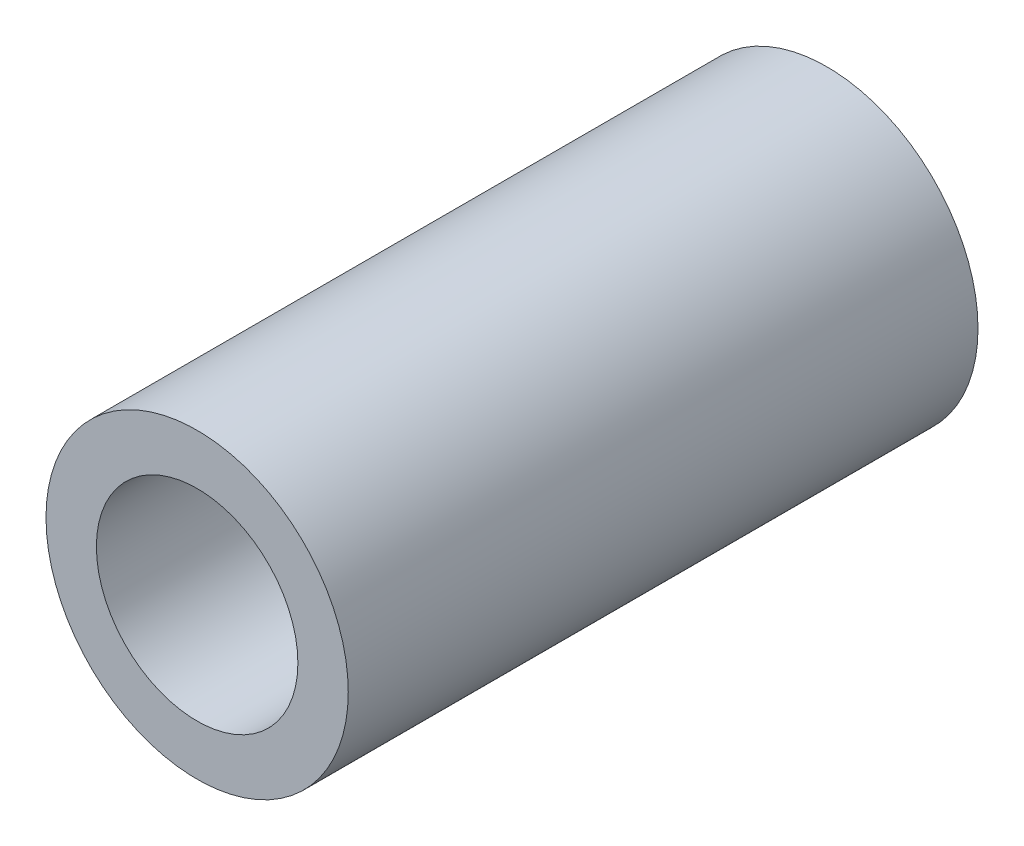
SolidWorks part; units mm, degrees
ref_plane "Front Plane" through (0, 0, 0) normal (0, 0, 1) x (1, 0, 0)
ref_plane "Top Plane" through (0, 0, 0) normal (0, 1, 0) x (1, 0, 0)
ref_plane "Right Plane" through (0, 0, 0) normal (1, 0, 0) x (0, 0, -1)
sketch "Sketch1" plane through (0, 0, 0) normal (0, 0, 1) x (1, 0, 0)
  circle A0 centre (0, 0) radius 1.6
  circle A1 centre (0, 0) radius 2.4
  dimension "D1" = 3.2
  dimension "D2" = 4.8
extrude "Boss-Extrude1" add sketch "Sketch1" along normal blind 10
